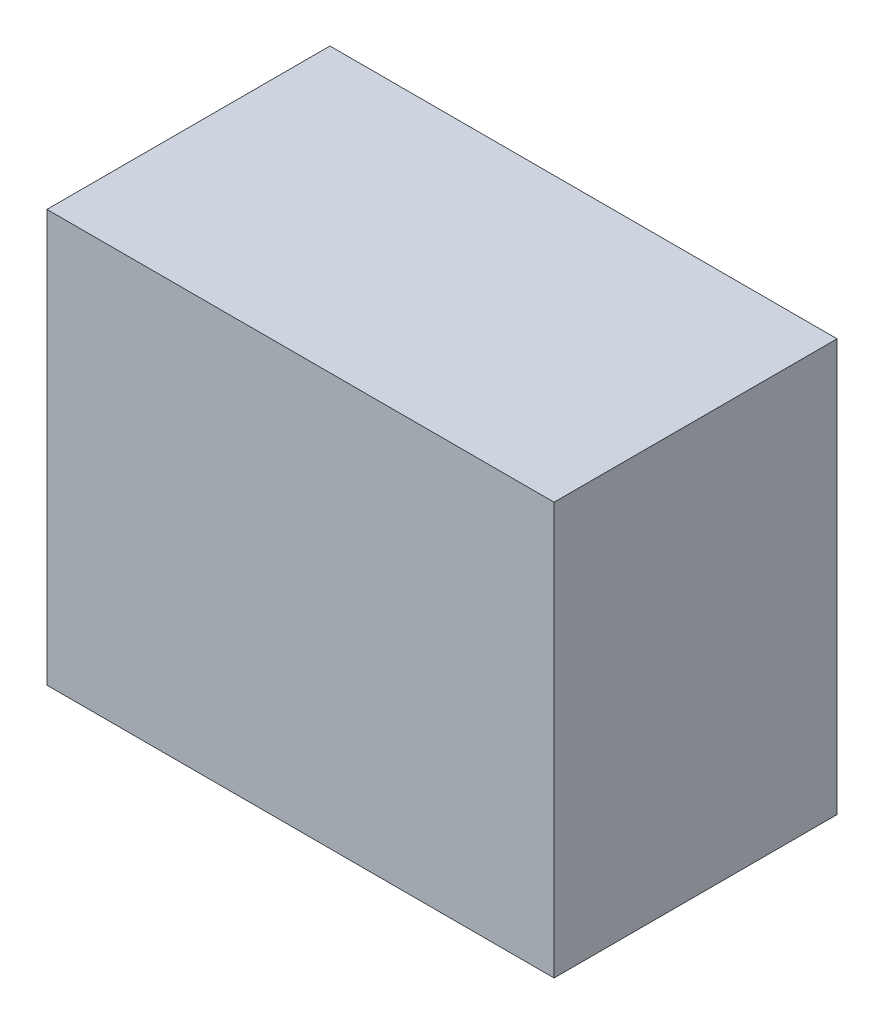
SolidWorks part; units mm, degrees
ref_plane "Front Plane" through (0, 0, 0) normal (0, 0, 1) x (1, 0, 0)
ref_plane "Top Plane" through (0, 0, 0) normal (0, 1, 0) x (1, 0, 0)
ref_plane "Right Plane" through (0, 0, 0) normal (1, 0, 0) x (0, 0, -1)
sketch "Sketch1" plane through (0, 0, 0) normal (0, 1, 0) x (1, 0, 0)
  line L1 (11.2, -6.25) -> (-11.2, -6.25)
  line L2 (11.2, -6.25) -> (11.2, 6.25)
  line L3 (11.2, 6.25) -> (-11.2, 6.25)
  line L4 (-11.2, -6.25) -> (-11.2, 6.25)
  line L5 (11.2, -6.25) -> (-11.2, 6.25) construction
  line L6 (11.2, 6.25) -> (-11.2, -6.25) construction
  point P0 (0, 0)
  dimension "D1" = 22.4
  dimension "D2" = 12.5
extrude "Boss-Extrude1" add sketch "Sketch1" along normal blind 18.2
